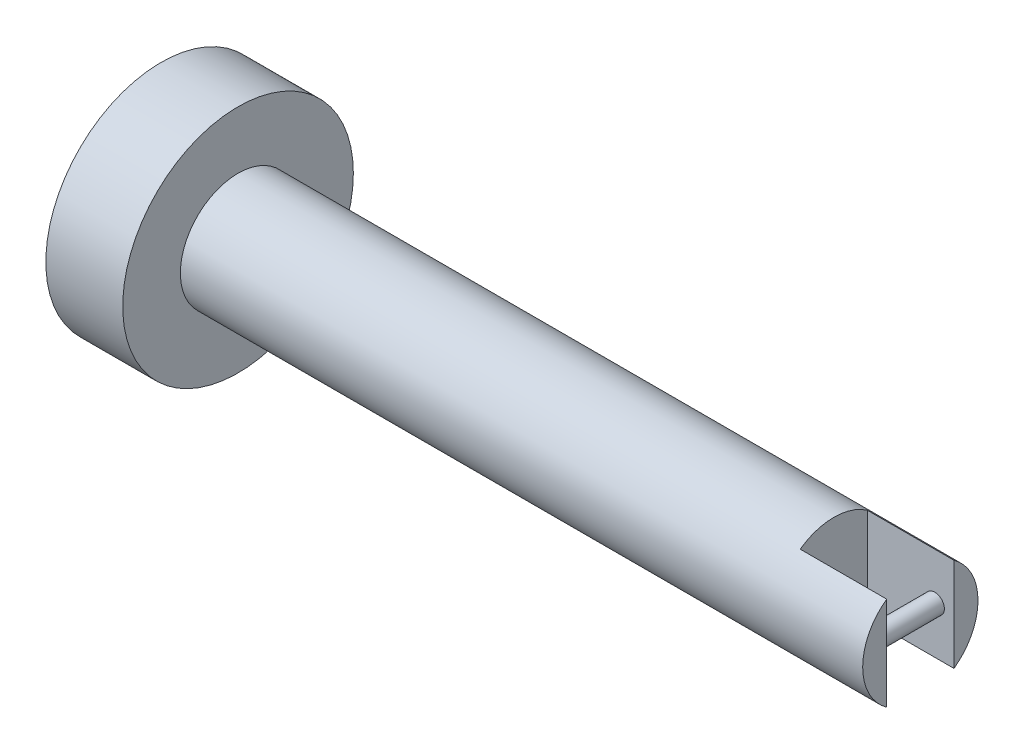
SolidWorks part; units mm, degrees
ref_plane "Front Plane" through (0, 0, 0) normal (0, 0, 1) x (1, 0, 0)
ref_plane "Top Plane" through (0, 0, 0) normal (0, 1, 0) x (1, 0, 0)
ref_plane "Right Plane" through (0, 0, 0) normal (1, 0, 0) x (0, 0, -1)
sketch "Sketch1" plane through (0, 0, 0) normal (1, 0, 0) x (0, 0, -1)
  circle A0 centre (0, 0) radius 60
extrude "Boss-Extrude1" add sketch "Sketch1" along normal blind 40 contours A0
sketch "Sketch2" plane through (40, 0, 0) normal (1, 0, 0) x (0, 0, -1)
  circle A0 centre (0, 0) radius 30
extrude "Boss-Extrude2" add sketch "Sketch2" along normal blind 355
sketch "Sketch3" plane through (395, 0, 0) normal (1, 0, 0) x (0, 0, -1)
  line L1 (-17.5, -34.4834) -> (17.5, -34.4834)
  line L2 (-17.5, -34.4834) -> (-17.5, 34.4834)
  line L3 (-17.5, 34.4834) -> (17.5, 34.4834)
  line L4 (17.5, -34.4834) -> (17.5, 34.4834)
extrude "Cut-Extrude1" cut sketch "Sketch3" against normal blind 45
sketch "Sketch4" plane through (0, 0, -17.5) normal (0, 0, 1) x (1, 0, 0)
  circle A0 centre (385, 0) radius 5
extrude "Boss-Extrude3" add sketch "Sketch4" along normal blind 35
